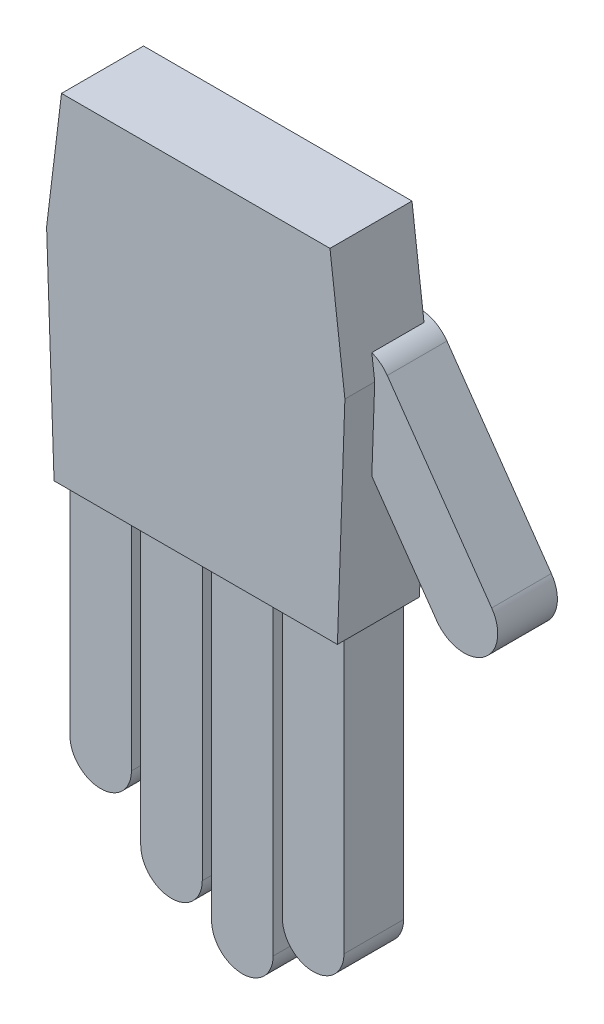
SolidWorks part; units mm, degrees
material "ABS"
ref_plane "Alzado" through (0, 0, 0) normal (0, 0, 1) x (1, 0, 0)
ref_plane "Planta" through (0, 0, 0) normal (0, 1, 0) x (1, 0, 0)
ref_plane "Vista lateral" through (0, 0, 0) normal (1, 0, 0) x (0, 0, -1)
ref_plane "Plane2" through (0, 0, -11) normal (0, 0, 1) x (1, 0, 0)
sketch "Sketch1" plane through (0, 0, -11) normal (0, 0, 1) x (1, 0, 0)
  line L0 (-36, -27) -> (36, -27)
  line L1 (36, -27) -> (40, -60)
  line L2 (40, -60) -> (38, -118)
  line L3 (38, -118) -> (-38, -118)
  line L4 (-38, -118) -> (-40, -60)
  line L5 (-40, -60) -> (-36, -27)
extrude "Palma" add sketch "Sketch1" along normal blind 22
ref_plane "Plane4" through (0, 0, -8) normal (0, 0, 1) x (1, 0, 0)
sketch "Sketch2" plane through (0, 0, -8) normal (0, 0, 1) x (1, 0, 0)
  line L0 (-28.5, -112) -> (-28.5, -178) construction
  line L1 (-20.25, -112) -> (-20.25, -178)
  line L2 (-36.75, -112) -> (-36.75, -178)
  arc A0 (-20.25, -112) -> (-36.75, -112) centre (-28.5, -112) ccw
  arc A1 (-36.75, -178) -> (-20.25, -178) centre (-28.5, -178) ccw
  point P2 (-28.5, -145)
  point P7 (0, 0)
extrude "Menique" add sketch "Sketch2" along normal blind 16
sketch "Sketch3" plane through (0, 0, -8) normal (0, 0, 1) x (1, 0, 0)
  line L0 (-9.5, -112) -> (-9.5, -194) construction
  line L1 (-1.25, -112) -> (-1.25, -194)
  line L2 (-17.75, -112) -> (-17.75, -194)
  arc A0 (-1.25, -112) -> (-17.75, -112) centre (-9.5, -112) ccw
  arc A1 (-17.75, -194) -> (-1.25, -194) centre (-9.5, -194) ccw
  point P2 (-9.5, -153)
  point P7 (0, 0)
extrude "Anular" add sketch "Sketch3" along normal blind 16
sketch "Sketch4" plane through (0, 0, -8) normal (0, 0, 1) x (1, 0, 0)
  line L0 (9.5, -112) -> (9.5, -202) construction
  line L1 (17.75, -112) -> (17.75, -202)
  line L2 (1.25, -112) -> (1.25, -202)
  arc A0 (17.75, -112) -> (1.25, -112) centre (9.5, -112) ccw
  arc A1 (1.25, -202) -> (17.75, -202) centre (9.5, -202) ccw
  point P2 (9.5, -157)
  point P7 (0, 0)
extrude "Medio" add sketch "Sketch4" along normal blind 16
sketch "Sketch5" plane through (0, 0, -8) normal (0, 0, 1) x (1, 0, 0)
  line L0 (28.5, -112) -> (28.5, -192) construction
  line L1 (36.75, -112) -> (36.75, -192)
  line L2 (20.25, -112) -> (20.25, -192)
  arc A0 (36.75, -112) -> (20.25, -112) centre (28.5, -112) ccw
  arc A1 (20.25, -192) -> (36.75, -192) centre (28.5, -192) ccw
  point P2 (28.5, -152)
  point P7 (0, 0)
extrude "Indice" add sketch "Sketch5" along normal blind 16
ref_plane "Plane6" through (0, 0, -13) normal (0, 0, 1) x (1, 0, 0)
sketch "Sketch6" plane through (0, 0, -13) normal (0, 0, 1) x (1, 0, 0)
  line L0 (36, -62) -> (64, -102) construction
  line L1 (43.3731, -56.8388) -> (71.3731, -96.8388)
  line L2 (28.6269, -67.1612) -> (56.6269, -107.1612)
  arc A0 (43.3731, -56.8388) -> (28.6269, -67.1612) centre (36, -62) ccw
  arc A1 (56.6269, -107.1612) -> (71.3731, -96.8388) centre (64, -102) ccw
  point P2 (50, -82)
  point P7 (0, 0)
extrude "Pulgar" add sketch "Sketch6" along normal blind 16
